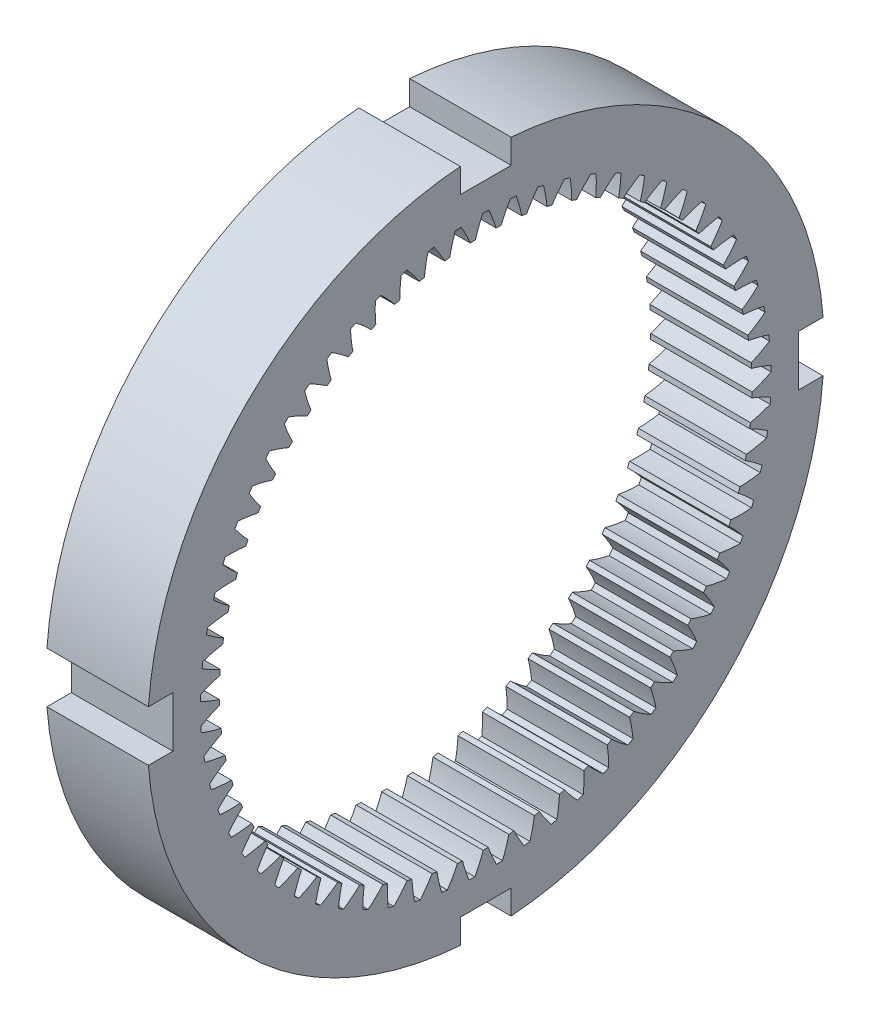
SolidWorks part; units mm, degrees
ref_plane "Plane1" through (0, 0, 0) normal (0, 0, 1) x (1, 0, 0)
ref_plane "Plane2" through (0, 0, 0) normal (0, 1, 0) x (1, 0, 0)
ref_plane "Plane3" through (0, 0, 0) normal (1, 0, 0) x (0, 0, -1)
sketch "HoldingSke" plane through (0, 0, 0) normal (0, 1, 0) x (1, 0, 0)
  line L0 (0, 0) -> (0.4226, -0.9063)
  line L1 (-15, 0) -> (100, 0) construction
  line L2 (0, 0) -> (-2.1039, 2.3779)
  line L3 (0, 0) -> (-11.863, 4.5341)
  line L4 (0, 0) -> (3.6497, 7.8269)
  line L5 (0, 0) -> (-23.7986, -8.8762)
  line L6 (0, 0) -> (-10.5278, -7.1032)
  line L7 (-2.1039, 2.3779) -> (3.3635, 27.1825)
  line L8 (-76.2, 3.3779) -> (-54.61, 3.3779)
  line L9 (-71.009, 38.7566) -> (-53.1078, 45.2721)
  line L10 (-76.2, 71.12) -> (104.1128, 71.12)
  line L11 (0, 0) -> (-12, 0)
  line L12 (-76.2, 101.6) -> (-76.162, 101.6)
  line L13 (24.9733, 27.94) -> (52.9518, 28.4284)
  line L14 (24.9733, 27.94) -> (24.9743, 27.94)
  line L15 (24.9733, 27.94) -> (100.4006, 29.5858)
  circle A0 centre (0, 0) radius 35
  circle A1 centre (0, 0) radius 12.7
  circle A2 centre (0, 0) radius 12.7
  dimension "MHD" = 25.4
  dimension "Hub_dia" = 25.4
  dimension "Diameter" = 70
  dimension "Num_teeth" = 65
  dimension "Pitch" = 1
  dimension "Overall_len" = 25.4
  dimension "Show_teeth" = 65
  dimension "Thickness" = 12.7
  dimension "OAL" = 25.4001
  dimension "T_dim" = 21.59
  dimension "Ap" = 20
  dimension "H" = 19.05
  dimension "Pitch_radius" = 180.3128
  dimension "Width" = 12
  dimension "Backlash" = 0.038
  dimension "Addendum_fac" = 1
  dimension "Dedendum_fac" = 1.25
  dimension "Clearance_fac" = 0.25
  dimension "Dedendum_add" = 0.001
  dimension "Module" = 1
sketch "BasProSke" plane through (0, 0, 0) normal (0, 1, 0) x (1, 0, 0)
  line L0 (-10, 0) -> (60, 0) construction
  line L1 (0, 31.5) -> (0, 35)
  line L2 (0, 31.5) -> (12, 31.5)
  line L3 (12, 31.5) -> (12, 35)
  line L4 (12, 35) -> (0, 35)
  dimension "Diameter" = 70
  dimension "Thickness" = 12
  dimension "Inside_diameter" = 63
revolve "Base-Revolve" add sketch "BasProSke" angle 360 about L0
sketch "TooCutSke" plane through (0, 0, 0) normal (1, 0, 0) x (0, 0, -1)
  line L3 (0.8803, 32.4881) -> (0.8803, 53.6633) construction
  line L4 (0, 0) -> (0, 59.563) construction
  line L5 (0, 0) -> (-3.3011, 68.2477) construction
  line L6 (-14.3506, 26.824) -> (36.4707, 29.2822) construction
  circle A0 centre (0, 0) radius 32.5 construction
  circle A1 centre (0, 0) radius 33.751 construction
  circle A2 centre (0, 0) radius 27.486 construction
  circle A3 centre (0, 0) radius 31.4746 construction
  arc A4 (1.2268, 31.4507) -> (0.3499, 33.7492) centre (-14.3506, 26.824) ccw
  arc A5 (1.2268, 31.4507) -> (-1.2268, 31.4507) centre (0, 0) ccw
  arc A6 (0.3499, 33.7492) -> (-0.3499, 33.7492) centre (0, 0) ccw
  arc A7 (-0.3499, 33.7492) -> (-1.2268, 31.4507) centre (14.3506, 26.824) ccw
  dimension "Pitch_dia" = 65
  dimension "Base_dia" = 54.972
  dimension "Root_dia" = 67.502
  dimension "Overcut_dia" = 62.9492
  dimension "Flank_rad" = 16.25
  dimension "Half_ang" = 2.769
  dimension "Half_CT" = 0.8803
extrude "ToothCut" cut sketch "TooCutSke" along normal through all
fillet "Breaks" [suppressed] radius 0.1
fillet "RootFillets" [suppressed] radius 0.251
pattern_circular "TeethCuts" count 65 every 5.538 about axis through (-10, 0, 0) along (1, 0, 0) of "RootFillets", "Breaks", "ToothCut"
sketch "Sketch1" plane through (12, 0, 0) normal (1, 0, 0) x (0, 0, -1)
  line L0 (0, 0) -> (0, 40) construction
  line L1 (39.8873, 3) -> (37, 3)
  line L3 (-3, 39.8873) -> (-3, 37)
  line L4 (-3, 37) -> (3, 37)
  line L5 (3, 39.8873) -> (3, 37)
  line L6 (37, 3) -> (37, -3)
  line L7 (39.8873, -3) -> (37, -3)
  line L8 (3, -39.8873) -> (3, -37)
  line L9 (3, -37) -> (-3, -37)
  line L10 (-3, -39.8873) -> (-3, -37)
  line L11 (-39.8873, -3) -> (-37, -3)
  line L12 (-37, -3) -> (-37, 3)
  line L13 (-39.8873, 3) -> (-37, 3)
  circle A0 centre (0, 0) radius 35 construction
  circle A1 centre (0, 0) radius 35
  arc A2 (-3, 39.8873) -> (-39.8873, 3) centre (0, 0) ccw
  arc A3 (-39.8873, -3) -> (-3, -39.8873) centre (0, 0) ccw
  arc A4 (3, -39.8873) -> (39.8873, -3) centre (0, 0) ccw
  arc A5 (39.8873, 3) -> (3, 39.8873) centre (0, 0) ccw
  point P9 (0, 37)
  point P25 (0, 0)
  dimension "D1" = 80
  dimension "D2" = 6
  dimension "D3" = 3
  dimension "D4" = 4
extrude "Boss-Extrude1" add sketch "Sketch1" against normal up to surface (12 mm away) up to face at (0, 0, 35)
equation "' \"Module@HoldingSke\" = 6.35"
equation "' \"Num_teeth@HoldingSke\" = 24"
equation "' \"Ap@HoldingSke\" =  14.5"
equation "' \"Ap@HoldingSke\" = 14.5"
equation "' \"Width@HoldingSke\" = 12"
equation "' \"Diameter@HoldingSke\" = 8 * 25.4"
equation "' \"Show_teeth@HoldingSke\" = 100"
equation "' \"Backlash@HoldingSke\" = 0.009 * 25.4"
equation "' \"Addendum_fac@HoldingSke\" = 1.0"
equation "' \"Dedendum_fac@HoldingSke\" = 1.25"
equation "' \"Dedendum_add@HoldingSke\" = 0.00005 * 25.4"
equation "' \"Clearance_fac@HoldingSke\" = 0.25"
equation "\"Pitch@HoldingSke\" = 1 / \"Module@HoldingSke\" "
equation "\"Overcut_dia@TooCutSke\" = (\"Num_teeth@HoldingSke\" - 2 * \"Addendum_fac@HoldingSke\") / \"Pitch@HoldingSke\" - 0.002 * 25.4"
equation "\"Pitch_dia@TooCutSke\" = \"Num_teeth@HoldingSke\" / \"Pitch@HoldingSke\""
equation "\"Base_dia@TooCutSke\" = \"Num_teeth@HoldingSke\" / \"Pitch@HoldingSke\" * cos((\"Ap@HoldingSke\"  * 3.14159265 / 180)) * 0.90"
equation "\"Root_dia@TooCutSke\" = \"Num_teeth@HoldingSke\"  / \"Pitch@HoldingSke\" + 2 *  \"Dedendum_fac@HoldingSke\"/ \"Pitch@HoldingSke\" + \"Dedendum_add@HoldingSke\" * 2"
equation "\"Half_ang@TooCutSke\" = 180 / \"Num_teeth@HoldingSke\""
equation "\"Half_CT@TooCutSke\" = \"Num_teeth@HoldingSke\" / \"Pitch@HoldingSke\" * sin((3.14159265 / 2 / \"Num_teeth@HoldingSke\")) / 2 + 10 * \"Backlash@HoldingSke\" / 4"
equation "\"Flank_rad@TooCutSke\" = \"Num_teeth@HoldingSke\" / \"Pitch@HoldingSke\" / 4"
equation "\"Radius@RootFillets\"= \"Clearance_fac@HoldingSke\" / \"Pitch@HoldingSke\" + \"Dedendum_add@HoldingSke\""
equation "\"Break_rad@Breaks\" = 0.02 / \"Pitch@HoldingSke\" * 5"
equation "\"Num_teeth@TeethCuts\" = int( \"Show_teeth@HoldingSke\" ) + 1"
equation "\"Num_teeth@TeethCuts\" = ((sgn( \"Num_teeth@TeethCuts\" - \"Num_teeth@HoldingSke\" )-1)*( \"Num_teeth@TeethCuts\" - \"Num_teeth@HoldingSke\" ))/-2+ \"Num_teeth@HoldingSke\""
equation "\"Num_teeth@TeethCuts\" = ((sgn( \"Num_teeth@TeethCuts\" - 2.0)+1)*( \"Num_teeth@TeethCuts\" - 2.0))/2 +2.0"
equation "\"Angle@TeethCuts\" = 360.0 / \"Num_teeth@HoldingSke\""
equation "\"Diameter@BasProSke\" = \"Num_teeth@HoldingSke\"  / \"Pitch@HoldingSke\" + 2 *  \"Dedendum_fac@HoldingSke\"/ \"Pitch@HoldingSke\" + \"Dedendum_add@HoldingSke\" * 2 + 0.002 * 25.4"
equation "\"Diameter@BasProSke\" = ((sgn( \"Diameter@BasProSke\"  - \"Diameter@HoldingSke\" )+1)*( \"Diameter@BasProSke\"  - \"Diameter@HoldingSke\" ))/2 + \"Diameter@HoldingSke\""
equation "\"Inside_diameter@BasProSke\" =  (\"Num_teeth@HoldingSke\" - 2 * \"Addendum_fac@HoldingSke\") / \"Pitch@HoldingSke\" "
equation "\"Thickness@BasProSke\"  = \"Width@HoldingSke\""
